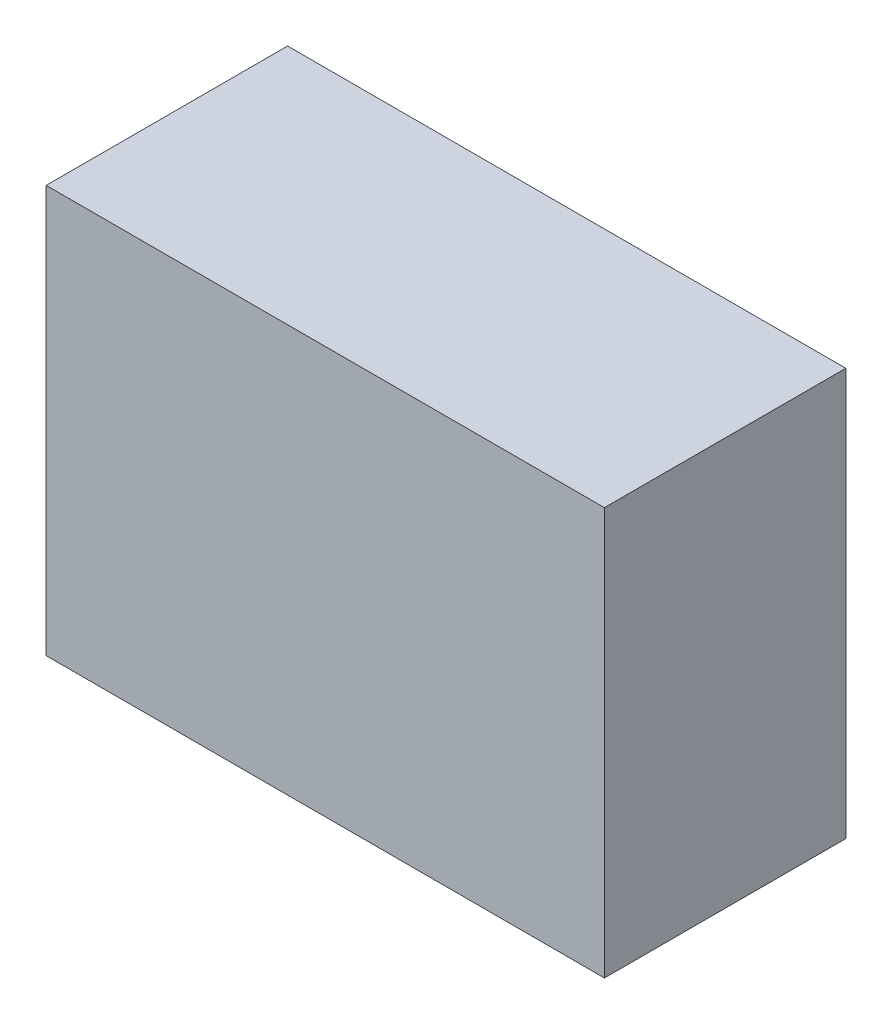
SolidWorks part; units mm, degrees
ref_plane "Front Plane" through (0, 0, 0) normal (0, 0, 1) x (1, 0, 0)
ref_plane "Top Plane" through (0, 0, 0) normal (0, 1, 0) x (1, 0, 0)
ref_plane "Right Plane" through (0, 0, 0) normal (1, 0, 0) x (0, 0, -1)
sketch "Sketch1" plane through (0, 0, 0) normal (0, 0, 1) x (1, 0, 0)
  line L1 (0, 0) -> (37, 0)
  line L2 (0, 0) -> (0, 27)
  line L3 (0, 27) -> (37, 27)
  line L4 (37, 0) -> (37, 27)
  dimension "D1" = 37
  dimension "D2" = 27
extrude "Profile" add sketch "Sketch1" along normal blind 16
equation "\"Profile_Depth\" = 16mm"
equation "\"D1@Profile\" = \"Profile_Depth\""
equation "\"EnvelopeWidth\" = 37mm"
equation "\"EnvelopeHeight\" = 27mm"
